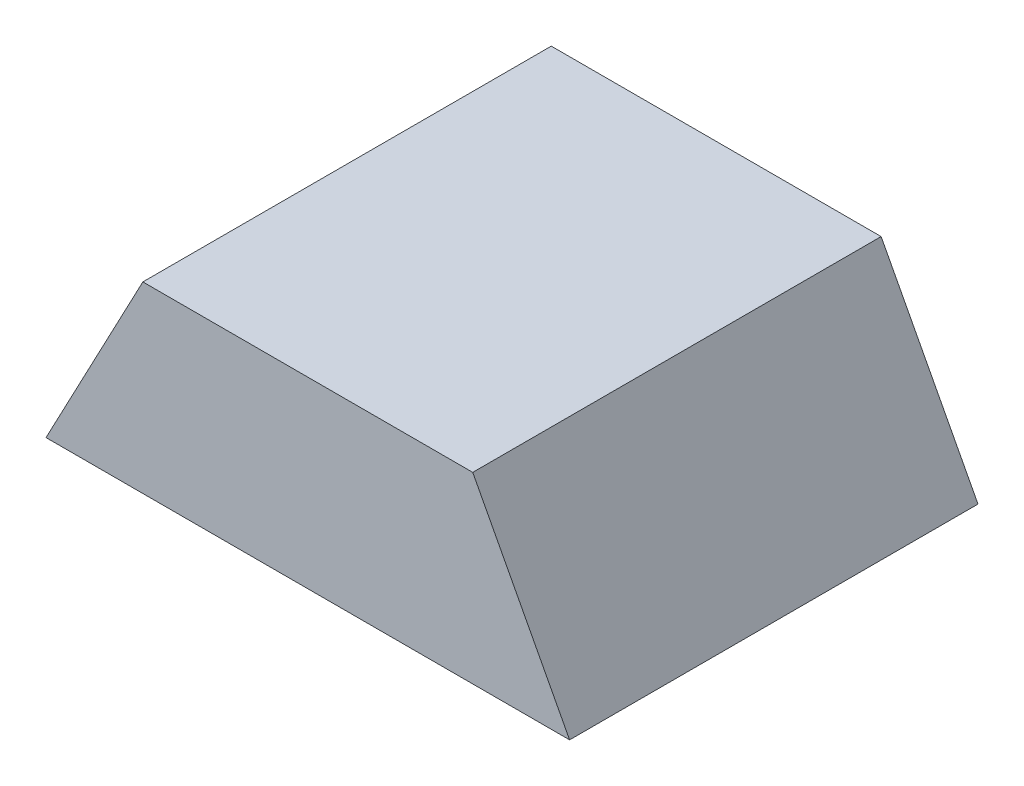
SolidWorks part; units mm, degrees
material "Teak"
ref_plane "Front Plane" through (0, 0, 0) normal (0, 0, 1) x (1, 0, 0)
ref_plane "Top Plane" through (0, 0, 0) normal (0, 1, 0) x (1, 0, 0)
ref_plane "Right Plane" through (0, 0, 0) normal (1, 0, 0) x (0, 0, -1)
sketch "Sketch2" plane through (0, 0, 0) normal (0, 0, 1) x (1, 0, 0)
  line L0 (2473.7312, 0) -> (3473.7312, 0)
  line L1 (3473.7312, 0) -> (3288.7312, 350)
  line L2 (3288.7312, 350) -> (2658.7312, 350)
  line L3 (2658.7312, 350) -> (2473.7312, 0)
  dimension "D1" = 1000
  dimension "D2" = 630
  dimension "D3" = 350
extrude "Boss-Extrude1" add sketch "Sketch2" along normal blind 780
shell "Shell1" thickness 6
